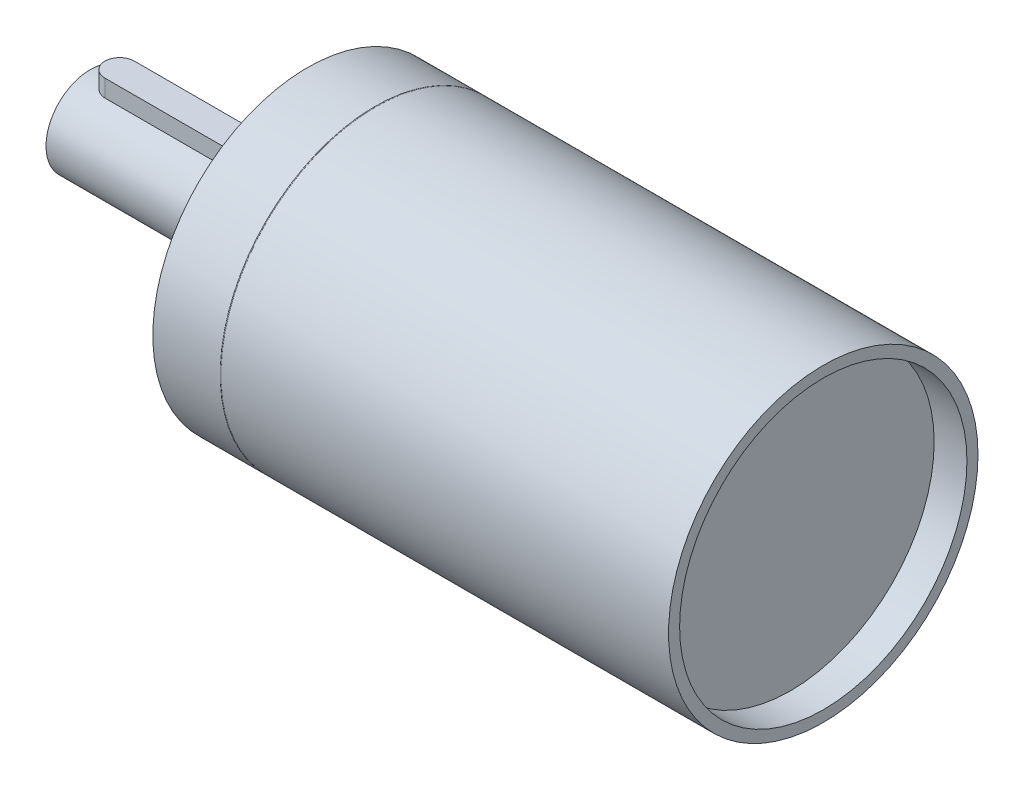
SolidWorks part; units mm, degrees
ref_plane "Front Plane" through (0, 0, 0) normal (0, 0, 1) x (1, 0, 0)
ref_plane "Top Plane" through (0, 0, 0) normal (0, 1, 0) x (1, 0, 0)
ref_plane "Right Plane" through (0, 0, 0) normal (1, 0, 0) x (0, 0, -1)
sketch "Sketch1" plane through (0, 0, 0) normal (0, 0, 1) x (1, 0, 0)
  line L0 (0, 21) -> (0, 0)
  line L1 (0, 0) -> (70, 0)
  line L2 (70, 0) -> (70, 21)
  line L3 (70, 21) -> (9.25, 21)
  line L4 (9.15, 21) -> (0, 21)
  line L5 (0, 0) -> (70, 0) construction
  arc A0 (9.25, 21) -> (9.15, 21) centre (9.2, 21.0866) cw
revolve "Revolve1" add sketch "Sketch1" angle 360 about L5
sketch "Sketch2" plane through (0, 0, 0) normal (-1, 0, 0) x (0, 0, 1)
  circle A0 centre (0, 0) radius 14
extrude "Boss-Extrude1" add sketch "Sketch2" along normal blind 3
sketch "Sketch3" plane through (-3, 0, 0) normal (-1, 0, 0) x (0, 0, 1)
  circle A0 centre (0, 0) radius 6
extrude "Boss-Extrude2" add sketch "Sketch3" along normal blind 26.5
sketch "Sketch4" plane through (-3, 0, 0) normal (-1, 0, 0) x (0, 0, 1)
  line L0 (0.2939, -7.6168) -> (0.2939, -5.9928)
  line L1 (-0.2939, -5.9928) -> (-0.2939, -7.6168)
  arc A0 (0.2939, -5.9928) -> (-0.2939, -5.9928) centre (0, 0) ccw
  arc A1 (-0.2939, -7.6168) -> (-2.8825, -5.9928) centre (0.2939, -3.8048) cw
  arc A2 (-2.8825, -5.9928) -> (2.8825, -5.9928) centre (0, 0) cw
  arc A3 (2.8825, -5.9928) -> (0.2939, -7.6168) centre (0.2939, -4.7418) cw
extrude "Boss-Extrude3" add sketch "Sketch4" along normal blind 1
ref_plane "Plane1" through (0, 8, 0) normal (0, 1, 0) x (-1, 0, 0)
sketch "Sketch5" plane through (0, 8, 0) normal (0, 1, 0) x (-1, 0, 0)
  line L0 (9.5, -2) -> (25.5, -2)
  line L1 (25.5, 2) -> (9.5, 2)
  arc A0 (25.5, -2) -> (25.5, 2) centre (25.5, 0) ccw
  arc A1 (9.5, 2) -> (9.5, -2) centre (9.5, 0) ccw
extrude "Boss-Extrude4" add sketch "Sketch5" against normal up to next
hole_wizard "Hole1" positions "Sketch7" profile "Sketch6" legacy
sketch "Sketch7" plane through (70, 0, 0) normal (1, 0, 0) x (0, 0, -1)
  point P0 (0, 0)
sketch "Sketch6" plane through (70, 0, 0) normal (0, 1, 0) x (0, 0, -1)
  line L0 (0, 0) -> (0, 4.45)
  line L1 (0, 4.45) -> (19.5, 4.45)
  line L2 (19.5, 4.45) -> (19.5, 0)
  line L3 (19.5, 0) -> (0, 0)
  line L4 (0, 110) -> (0, -10) construction
  dimension "Diameter" = 39
  dimension "Depth" = 4.45
hole_wizard "Hole2" positions "Sketch9" profile "Sketch8" legacy
sketch "Sketch9" plane through (0, 0, 0) normal (-1, 0, 0) x (0, 0, 1)
  point P0 (-17.5, 0)
sketch "Sketch8" plane through (0, 0, -17.5) normal (0, 1, 0) x (0, 0, 1)
  line L0 (0, 0) -> (0, 6.9914)
  line L1 (0, 6.9914) -> (1.65, 6)
  line L2 (1.65, 6) -> (1.65, 0)
  line L4 (1.65, 0) -> (0, 0)
  line L6 (0, 6.9914) -> (-1.65, 6) construction
  line L7 (0, -4.2442) -> (0, 117.3081) construction
  dimension "Diameter" = 3.3
  dimension "Depth" = 6
  dimension "Drill Angle" = 118
hole_wizard "Hole3" positions "Sketch11" profile "Sketch10" legacy
sketch "Sketch11" plane through (0, 0, 0) normal (-1, 0, 0) x (0, 0, 1)
  point P0 (0, -17.5)
sketch "Sketch10" plane through (0, -17.5, 0) normal (0, 1, 0) x (0, 0, 1)
  line L0 (0, 0) -> (0, 6.9914)
  line L1 (0, 6.9914) -> (1.65, 6)
  line L2 (1.65, 6) -> (1.65, 0)
  line L4 (1.65, 0) -> (0, 0)
  line L6 (0, 6.9914) -> (-1.65, 6) construction
  line L7 (0, -4.2442) -> (0, 117.3081) construction
  dimension "Diameter" = 3.3
  dimension "Depth" = 6
  dimension "Drill Angle" = 118
hole_wizard "Hole4" positions "Sketch13" profile "Sketch12" legacy
sketch "Sketch13" plane through (0, 0, 0) normal (-1, 0, 0) x (0, 0, 1)
  point P0 (17.5, 0)
sketch "Sketch12" plane through (0, 0, 17.5) normal (0, 1, 0) x (0, 0, 1)
  line L0 (0, 0) -> (0, 6.9914)
  line L1 (0, 6.9914) -> (1.65, 6)
  line L2 (1.65, 6) -> (1.65, 0)
  line L4 (1.65, 0) -> (0, 0)
  line L6 (0, 6.9914) -> (-1.65, 6) construction
  line L7 (0, -4.2442) -> (0, 117.3081) construction
  dimension "Diameter" = 3.3
  dimension "Depth" = 6
  dimension "Drill Angle" = 118
hole_wizard "Hole5" positions "Sketch15" profile "Sketch14" legacy
sketch "Sketch15" plane through (0, 0, 0) normal (-1, 0, 0) x (0, 0, 1)
  point P0 (0, 17.5)
sketch "Sketch14" plane through (0, 17.5, 0) normal (0, 1, 0) x (0, 0, 1)
  line L0 (0, 0) -> (0, 6.9914)
  line L1 (0, 6.9914) -> (1.65, 6)
  line L2 (1.65, 6) -> (1.65, 0)
  line L4 (1.65, 0) -> (0, 0)
  line L6 (0, 6.9914) -> (-1.65, 6) construction
  line L7 (0, -4.2442) -> (0, 117.3081) construction
  dimension "Diameter" = 3.3
  dimension "Depth" = 6
  dimension "Drill Angle" = 118
hole_wizard "Hole6" positions "Sketch17" profile "Sketch16" legacy
sketch "Sketch17" plane through (-29.5, 0, 0) normal (-1, 0, 0) x (0, 0, 1)
  point P0 (0, 0)
sketch "Sketch16" plane through (-29.5, 0, 0) normal (0, 1, 0) x (0, 0, 1)
  line L0 (0, 0) -> (0, 2.3)
  line L1 (0, 2.3) -> (0.625, 1.9392)
  line L2 (0.625, 1.9392) -> (0.625, 1.2124)
  line L3 (0.625, 1.2124) -> (1.325, 0)
  line L4 (1.325, 0) -> (0, 0)
  line L5 (0, -14.3089) -> (0, 102.4216) construction
  line L6 (0, 2.3) -> (-0.625, 1.9392) construction
  line L7 (-0.625, 1.2124) -> (-1.325, 0) construction
  dimension "Diameter" = 1.25
  dimension "Depth" = 1.9392
  dimension "C-Sink Diameter" = 2.65
  dimension "C-Sink Angle" = 60
  dimension "Drill Angle" = 120
